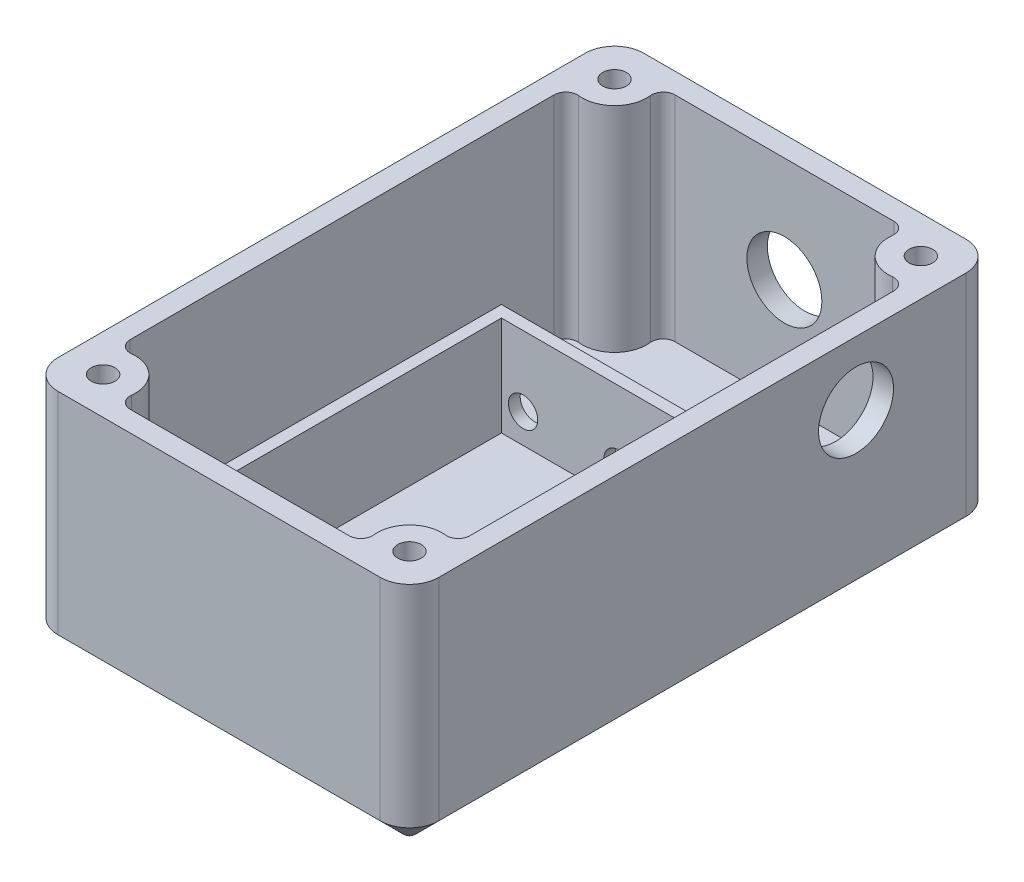
SolidWorks part; units mm, degrees
ref_plane "Front Plane" through (0, 0, 0) normal (0, 0, 1) x (1, 0, 0)
ref_plane "Top Plane" through (0, 0, 0) normal (0, 1, 0) x (1, 0, 0)
ref_plane "Right Plane" through (0, 0, 0) normal (1, 0, 0) x (0, 0, -1)
sketch "Sketch3" plane through (0, 0, 0) normal (0, 1, 0) x (1, 0, 0)
  line L1 (-32.5, 50) -> (32.5, 50)
  line L2 (-32.5, 50) -> (-32.5, -50)
  line L3 (-32.5, -50) -> (32.5, -50)
  line L4 (32.5, 50) -> (32.5, -50)
  line L5 (-32.5, 50) -> (32.5, -50) construction
  line L6 (-32.5, -50) -> (32.5, 50) construction
  point P0 (0, 0)
  dimension "D1" = 65
  dimension "D2" = 100
extrude "Boss-Extrude1" add sketch "Sketch3" along normal blind 40
sketch "Sketch8" plane through (0, 40, 0) normal (0, 1, 0) x (1, 0, 0)
  line L0 (32.5, 50) -> (-32.5, 50) construction
  line L1 (-32.5, 50) -> (-32.5, -50) construction
  line L2 (-32.5, -50) -> (32.5, -50) construction
  line L3 (32.5, -50) -> (32.5, 50) construction
  point P0 (-26.15, 43.65)
  point P1 (26.15, 43.65)
  point P2 (26.15, -43.65)
  point P3 (-26.15, -43.65)
  dimension "D1" = 6.35
  dimension "D2" = 6.35
  dimension "D3" = 6.35
  dimension "D4" = 6.35
hole_wizard "#21 (0.159) Diameter Hole1" positions "Sketch12" profile "Sketch13" hole size "#21" standard "ANSI Inch" end condition up to next
sketch "Sketch12" plane through (0, 40, 0) normal (0, 1, 0) x (1, 0, 0)
  point P0 (-26.15, 43.65)
  point P3 (26.15, 43.65)
  point P6 (26.15, -43.65)
  point P9 (-26.15, -43.65)
sketch "Sketch13" plane through (-26.15, 40, -43.65) normal (1, 0, 0) x (0, 0, 1)
  line L0 (0, 0) -> (0, 40)
  line L1 (0, 40) -> (2.0193, 40)
  line L2 (2.0193, 40) -> (2.0193, 0)
  line L5 (2.0193, 0) -> (0, 0)
  line L11 (0, -6.35) -> (0, 107.95) construction
  dimension "Thru Hole Dia." = 4.0386
  dimension "Thru Hole Depth" = 40
shell "Shell1" thickness 3.5
fillet "Fillet1" radius 2 8 edges at (21.4235, 21.75, 46.5) (29, 21.75, 38.9235) (29, 21.75, -38.9235) (21.4235, 21.75, -46.5) (-21.4235, 21.75, -46.5) (-29, 21.75, 38.9235) (-21.4235, 21.75, 46.5) (-29, 21.75, -38.9235)
sketch "Sketch14" plane through (0, 0, 0) normal (0, 1, 0) x (1, 0, 0)
  line L0 (-2.3838, -37) -> (-15.3838, -37)
  line L1 (15.6162, -37) -> (2.6162, -37)
  line L2 (15.6162, -37) -> (15.6162, -44)
  line L3 (15.6162, -44) -> (2.6162, -44)
  line L4 (2.6162, -37) -> (2.6162, -44)
  line L5 (-2.3838, -44) -> (-15.3838, -44)
  line L6 (-2.3838, -37) -> (-2.3838, -44)
  line L7 (-15.3838, -37) -> (-15.3838, -44)
  line L8 (-2.3838, 23.1885) -> (-15.3838, 23.1885)
  line L9 (-15.3838, 30.1885) -> (-15.3838, 23.1885)
  line L10 (15.6162, 30.1885) -> (15.6162, 23.1885)
  line L11 (-2.3838, 30.1885) -> (-15.3838, 30.1885)
  line L12 (-2.3838, 30.1885) -> (-2.3838, 23.1885)
  line L13 (2.6162, 30.1885) -> (2.6162, 23.1885)
  line L14 (15.6162, 30.1885) -> (2.6162, 30.1885)
  line L15 (15.6162, 23.1885) -> (2.6162, 23.1885)
  dimension "D1" = 7
  dimension "D2" = 13
  dimension "D3" = 13
  dimension "D4" = 13
  dimension "D5" = 13
  dimension "D6" = 37
  dimension "D7" = 37
extrude "Cut-Extrude1" cut sketch "Sketch14" along normal blind 10
fillet "Fillet2" radius 5 4 edges at (-32.5, 20, -50) (32.5, 20, -50) (32.5, 20, 50) (-32.5, 20, 50)
chamfer "Chamfer2" distance 4 angle 45 5 edges at (-31.0355, 0, -48.5355) (-31.0355, 0, 48.5355) (31.0355, 0, -48.5355) (31.0355, 0, 48.5355) (32.5, 0, 0)
sketch "Sketch15" plane through (0, 0, -50) normal (0, 0, -1) x (-1, 0, 0)
  line L2 (-27.5, 40) -> (-27.5, 4) construction
  circle A2 centre (0, 22) radius 6.4
  point P5 (-27.5, 22)
  dimension "D1" = 12.8
extrude "Cut-Extrude3" cut sketch "Sketch15" against normal blind 10
sketch "Sketch17" plane through (32.5, 0, 0) normal (1, 0, 0) x (0, 0, -1)
  circle A0 centre (26.2334, 29.1136) radius 6.4
  dimension "D1" = 12.8
extrude "Cut-Extrude6" cut sketch "Sketch17" against normal blind 10 contours A0
sketch "Sketch18" plane through (0, 3.5, 0) normal (0, 1, 0) x (1, 0, 0)
  line L0 (18.6789, 46.5) -> (-18.6789, 46.5) construction
  line L1 (2.9629, 35.6605) -> (3, 35.6605)
  line L2 (-3, 35.6605) -> (-2.9629, 35.6605)
  line L3 (-3, 35.6605) -> (-3, 31.6605)
  line L4 (-3, 31.6605) -> (3, 31.6605)
  line L5 (3, 35.6605) -> (3, 31.6605)
  line L6 (-3, 35.6605) -> (3, 31.6605) construction
  line L7 (-3, 31.6605) -> (3, 35.6605) construction
  arc A1 (2.9629, 35.6605) -> (-2.9629, 35.6605) centre (0, 40.5884) ccw
  point P6 (0, 46.5)
  point P7 (0, 33.6605)
  dimension "D1" = 11.5
  dimension "D2" = 6
  dimension "D3" = 4
extrude "Cut-Extrude8" cut sketch "Sketch18" against normal blind 1.5
sketch "Sketch20" plane through (0, 3.5, 0) normal (0, 1, 0) x (1, 0, 0)
  line L0 (29, -36.1789) -> (29, 36.1789) construction
  line L1 (-22, 20.1941) -> (29, 20.1941)
  line L2 (-22, 20.1941) -> (-22, -32.8059)
  line L3 (-22, -32.8059) -> (29, -32.8059)
  line L4 (29, 20.1941) -> (29, -32.8059)
  dimension "D1" = 53
  dimension "D2" = 51
extrude "Boss-Extrude3" add sketch "Sketch20" along normal blind 17
sketch "Sketch22" plane through (0, 20.5, 0) normal (0, 1, 0) x (1, 0, 0)
  line L0 (29, -32.8059) -> (29, 20.1941) construction
  line L1 (29, 18.1941) -> (-20, 18.1941)
  line L2 (29, 18.1941) -> (29, -30.8059)
  line L3 (29, -30.8059) -> (-20, -30.8059)
  line L4 (-20, 18.1941) -> (-20, -30.8059)
  line L6 (-22, -32.8059) -> (29, -32.8059) construction
  dimension "D1" = 49
  dimension "D2" = 49
  dimension "D3" = 2
extrude "Cut-Extrude9" cut sketch "Sketch22" against normal blind 17
sketch "Sketch23" plane through (0, 0, -18.1941) normal (0, 0, 1) x (1, 0, 0)
  line L0 (29, 3.5) -> (-20, 3.5) construction
  line L1 (18.6789, 3.5) -> (-18.6789, 3.5) construction
  circle A0 centre (-16.3, 8.5) radius 2.5
  circle A1 centre (0, 8.5) radius 2.5
  circle A2 centre (16.3, 8.5) radius 2.5
  point P8 (0, 3.5)
  dimension "D1" = 5
  dimension "D2" = 5
  dimension "D3" = 5
  dimension "D4" = 5
  dimension "D5" = 16.3
  dimension "D6" = 16.3
extrude "Cut-Extrude10" cut sketch "Sketch23" against normal blind 3
